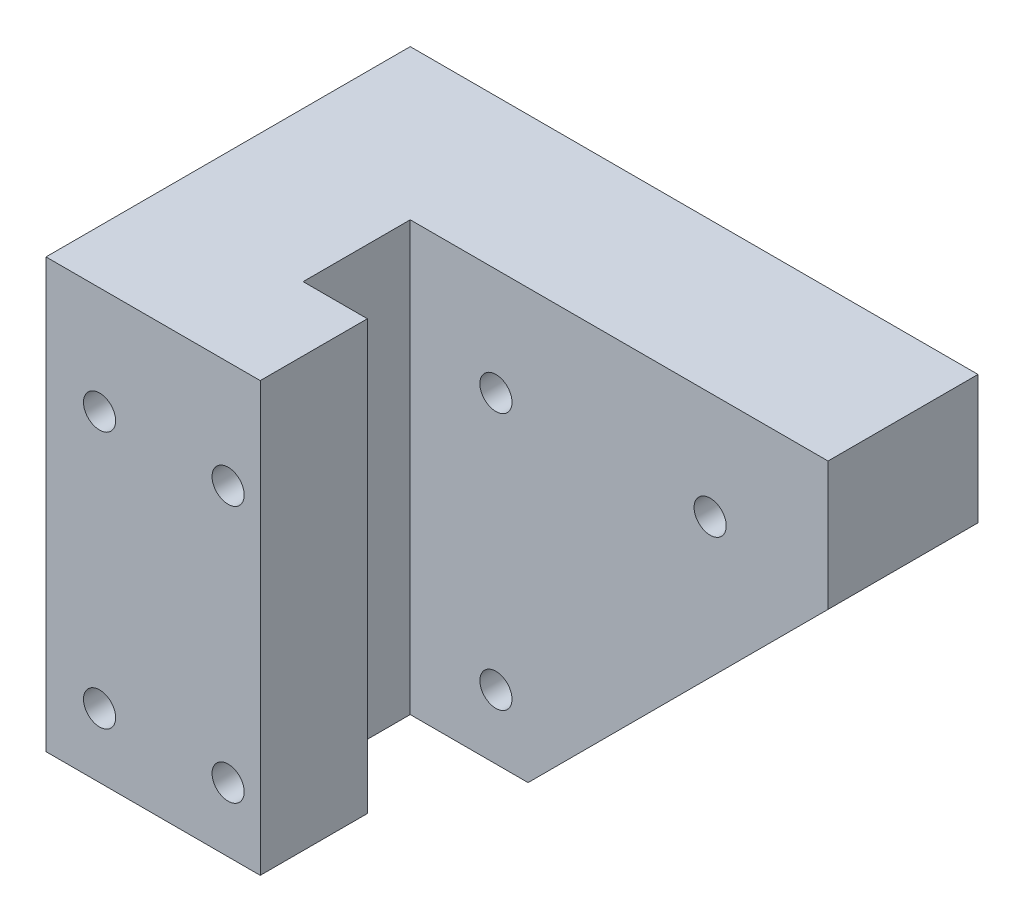
SolidWorks part; units mm, degrees
ref_plane "前视基准面" through (0, 0, 0) normal (0, 0, 1) x (1, 0, 0)
ref_plane "上视基准面" through (0, 0, 0) normal (0, 1, 0) x (1, 0, 0)
ref_plane "右视基准面" through (0, 0, 0) normal (1, 0, 0) x (0, 0, -1)
other "Configuration Table"
sketch "草图1" plane through (0, 0, 0) normal (0, 0, 1) x (1, 0, 0)
  line L1 (0, 0) -> (20, 0)
  line L2 (0, 0) -> (0, 40)
  line L3 (0, 40) -> (20, 40)
  line L4 (20, 0) -> (20, 40)
  dimension "D1" = 20
  dimension "D2" = 40
extrude "凸台-拉伸1" add sketch "草图1" along normal blind 34
sketch "草图2" plane through (0, 0, 34) normal (0, 0, 1) x (1, 0, 0)
  line L0 (0, 40) -> (0, 0) construction
  line L1 (0, 0) -> (20, 0) construction
  circle A0 centre (5, 30) radius 1.5
  circle A1 centre (5, 6) radius 1.5
  dimension "D1" = 3
  dimension "D2" = 3
  dimension "D3" = 5
  dimension "D4" = 24
  dimension "D5" = 6
extrude "切除-拉伸1" cut sketch "草图2" against normal through all
sketch "草图3" plane through (0, 0, 34) normal (0, 0, 1) x (1, 0, 0)
  line L0 (0, 0) -> (20, 0) construction
  line L1 (20, 0) -> (53, 0)
  line L2 (20, 0) -> (20, 40)
  line L3 (20, 40) -> (53, 40)
  line L4 (53, 0) -> (53, 40)
  line L5 (20, 40) -> (0, 40) construction
  line L6 (20, 0) -> (20, 40) construction
  dimension "D1" = 33
extrude "凸台-拉伸2" add sketch "草图3" along normal blind 14 from surface at -34 starting at face at (6.5, 30, 0)
sketch "草图4" plane through (0, 0, 0) normal (0, 0, -1) x (-1, 0, 0)
  line L5 (-25, 0) -> (-53, 0)
  line L6 (-53, 0) -> (-53, 28)
  line L7 (-53, 40) -> (-53, 0) construction
  line L8 (-53, 28) -> (-25, 0)
  dimension "D1" = 28
  dimension "D2" = 28
extrude "切除-拉伸2" cut sketch "草图4" against normal through all
sketch "草图5" plane through (0, 0, 0) normal (0, 0, -1) x (-1, 0, 0)
  line L0 (-22, 30) -> (-5, 30) construction
  line L1 (-22, 6) -> (-5, 6) construction
  circle A0 centre (-22, 30) radius 1.5
  circle A1 centre (-22, 6) radius 1.5
  circle A2 centre (-5, 30) radius 1.5 construction
  circle A3 centre (-42, 30) radius 1.5
  dimension "D1" = 3
  dimension "D2" = 3
  dimension "D4" = 3
  dimension "D3" = 17
  dimension "D5" = 20
extrude "切除-拉伸3" cut sketch "草图5" against normal through all
sketch "草图6" plane through (0, 0, 0) normal (0, -1, 0) x (1, 0, 0)
  line L1 (20, 14) -> (14, 14)
  line L2 (20, 14) -> (20, 24)
  line L3 (20, 24) -> (14, 24)
  line L4 (14, 14) -> (14, 24)
  dimension "D1" = 6
  dimension "D2" = 10
extrude "切除-拉伸4" cut sketch "草图6" against normal through all
sketch "草图7" plane through (0, 0, 34) normal (0, 0, 1) x (1, 0, 0)
  line L0 (17, 6) -> (5, 6) construction
  line L1 (17, 30) -> (5, 30) construction
  circle A0 centre (17, 30) radius 1.5
  circle A1 centre (17, 6) radius 1.5
  circle A2 centre (5, 30) radius 1.5 construction
  circle A3 centre (5, 6) radius 1.5 construction
  dimension "D1" = 3
  dimension "D2" = 3
  dimension "D3" = 12
extrude "切除-拉伸5" cut sketch "草图7" against normal up to surface (10 mm away) up to face at (17, 20, 24)
